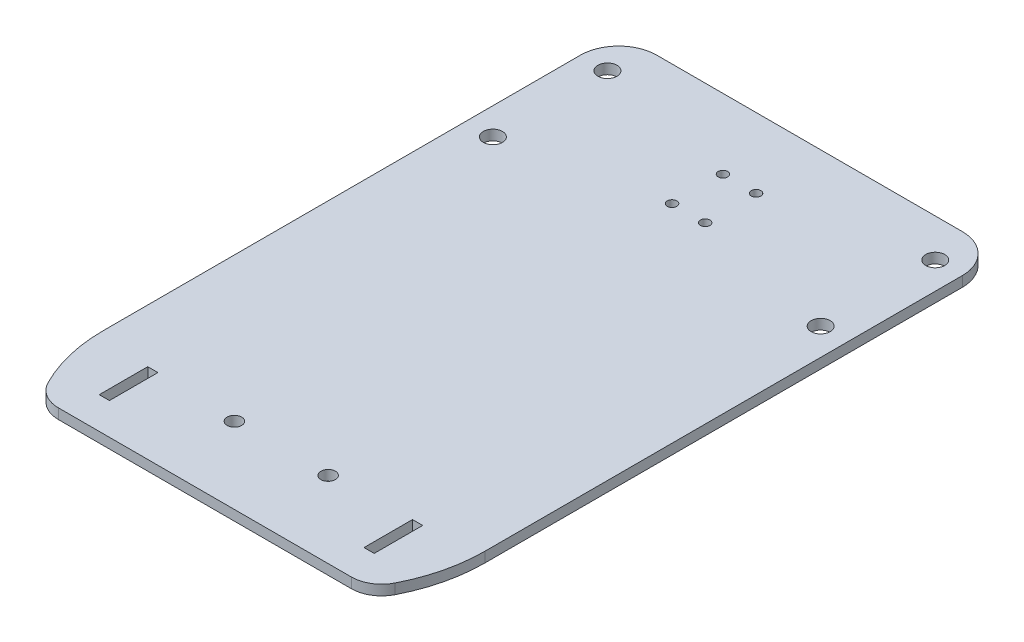
SolidWorks part; units mm, degrees
other "main"
material "Skleněné vlákno-A"
ref_plane "Přední rovina" through (0, 0, 0) normal (0, 0, 1) x (1, 0, 0)
ref_plane "Horní rovina" through (0, 0, 0) normal (0, 1, 0) x (1, 0, 0)
ref_plane "Pravá rovina" through (0, 0, 0) normal (1, 0, 0) x (0, 0, -1)
sketch "Skica1" plane through (0, 0, 0) normal (0, 1, 0) x (1, 0, 0)
  line L1 (-30, 0) -> (30, 0)
  line L2 (-30, 0) -> (-30, -95)
  line L3 (-30, -95) -> (30, -95)
  line L4 (30, 0) -> (30, -95)
  dimension "D1" = 60
  dimension "D2" = 95
extrude "Přidat vysunutím1" add sketch "Skica1" along normal mid plane 1.6
sketch "Skica3" plane through (0, 0.8, 0) normal (0, 1, 0) x (1, 0, 0)
  line L0 (-23, -81) -> (-30, -81) construction
  line L1 (-30, 0) -> (-30, -95) construction
  line L2 (-30, -95) -> (30, -95) construction
  line L3 (-23, -81) -> (-23, -95) construction
  line L4 (0, -95) -> (0, 0) construction
  line L5 (30, 0) -> (-30, 0) construction
  line L6 (-24, 0) -> (24, 0)
  line L7 (-30, -95) -> (30, -95) construction
  line L8 (-23, -95) -> (23, -95)
  line L9 (-30, -81) -> (-30, -6)
  line L10 (30, -81) -> (30, -6)
  arc A0 (-24, 0) -> (-30, -6) centre (-24, -6) ccw
  arc A1 (24, 0) -> (30, -6) centre (24, -6) cw
  arc A2 (-23, -95) -> (-27.2472, -92.4045) centre (-23, -90.2273) cw
  arc A3 (-27.2472, -92.4045) -> (-30, -81) centre (-5, -81) cw
  arc A4 (27.2472, -92.4045) -> (30, -81) centre (5, -81) ccw
  arc A5 (23, -95) -> (27.2472, -92.4045) centre (23, -90.2273) ccw
  dimension "D3" = 6
  dimension "D4" = 25
  dimension "D1" = 14
  dimension "D2" = 7
extrude "Odebrat vysunutím2" cut sketch "Skica3" against normal through all flip side to cut
sketch "Skica2" plane through (0, 0.8, 0) normal (0, 1, 0) x (1, 0, 0)
  line L1 (-20, -82.38) -> (-21.6, -82.38)
  line L2 (-20, -82.38) -> (-20, -90)
  line L3 (-20, -90) -> (-21.6, -90)
  line L4 (-21.6, -82.38) -> (-21.6, -90)
  line L5 (-23, -95) -> (23, -95) construction
  line L6 (0, 0) -> (0, -167.2259) construction
  line L7 (24, 0) -> (-24, 0) construction
  line L8 (21.6, -82.38) -> (21.6, -90)
  line L9 (20, -90) -> (21.6, -90)
  line L10 (20, -82.38) -> (20, -90)
  line L11 (20, -82.38) -> (21.6, -82.38)
  dimension "D1" = 40
  dimension "D2" = 1.6
  dimension "D3" = 7.62
  dimension "D4" = 5
extrude "Odebrat vysunutím1" cut sketch "Skica2" against normal through all
sketch "Skica4" plane through (0, 0.8, 0) normal (0, 1, 0) x (1, 0, 0)
  line L0 (0, 0) -> (0, -25.1622) construction
  circle A0 centre (-25.75, -6) radius 1.5
  circle A1 centre (-25.75, -24) radius 1.5
  circle A2 centre (-25.75, -24) radius 1.25 construction
  circle A3 centre (-25.75, -6) radius 1.25 construction
  circle A4 centre (25.75, -24) radius 1.5
  circle A5 centre (25.75, -6) radius 1.5
  dimension "D1" = 3
extrude "Odebrat vysunutím3" cut sketch "Skica4" against normal through all
sketch "Skica5" plane through (0, -0.8, 0) normal (0, -1, 0) x (1, 0, 0)
  circle A0 centre (-7.366, 83) radius 1.143 construction
  circle A1 centre (-7.366, 83) radius 1.143
  circle A2 centre (7.366, 83) radius 1.143 construction
  circle A3 centre (7.366, 83) radius 1.143
extrude "Odebrat vysunutím4" cut sketch "Skica5" against normal through all
sketch "Skica6" plane through (0, -0.8, 0) normal (0, -1, 0) x (1, 0, 0)
  line L0 (-20, 88.73) -> (-18.73, 88.73)
  line L1 (-20, 86.19) -> (-18.73, 86.19)
  line L3 (-20, 83.65) -> (-18.73, 83.65)
  line L4 (-20, 95.9658) -> (-18.73, 95.9658) construction
  line L5 (-20.8, 82.38) -> (-20.8, 88.1097) construction
  line L6 (-20, 82.38) -> (-21.6, 82.38) construction
  line L7 (-21.6, 83.65) -> (-22.87, 83.65)
  line L8 (-21.6, 86.19) -> (-22.87, 86.19)
  line L9 (-21.6, 88.73) -> (-22.87, 88.73)
  line L10 (0, 0) -> (0, 32.2699) construction
  line L11 (21.6, 88.73) -> (22.87, 88.73)
  line L12 (21.6, 86.19) -> (22.87, 86.19)
  line L13 (21.6, 83.65) -> (22.87, 83.65)
  line L14 (20, 83.65) -> (18.73, 83.65)
  line L15 (20, 86.19) -> (18.73, 86.19)
  line L16 (20, 88.73) -> (18.73, 88.73)
sketch "Skica7" [suppressed] plane through (0, 0.8, 0) normal (0, 1, 0) x (1, 0, 0)
  line L0 (-26.5, -29) -> (26.5, -29) construction
  line L1 (-29.5, -27) -> (29.5, -27)
  line L2 (-29.5, -27) -> (-29.5, -61)
  line L3 (-29.5, -61) -> (29.5, -61)
  line L4 (29.5, -27) -> (29.5, -61)
  line L5 (26.5, -59) -> (-26.5, -59) construction
  line L6 (-27.5, -58) -> (-27.5, -30) construction
  line L7 (-30, -6) -> (-30, -81) construction
  line L8 (27.5, -30) -> (27.5, -58) construction
  line L9 (-19, -22.5) -> (-29.5, -22.5) construction
  line L10 (-4.8, -7.5) -> (-21.5, -7.5)
  line L11 (-4.8, -7.5) -> (-4.8, -22.5)
  line L12 (-4.8, -22.5) -> (-21.5, -22.5)
  line L13 (-21.5, -7.5) -> (-21.5, -5.95) construction
  line L14 (-29.5, -7.5) -> (-19, -7.5) construction
  line L15 (-4.8, -17.5) -> (-4.8, -12.5) construction
  line L16 (-21.5, -7.5) -> (-21.5, -5.95)
  line L17 (-30, -6) -> (-30, -24.05)
  line L18 (-21.5, -24.05) -> (-21.5, -22.5) construction
  line L19 (-21.5, -24.05) -> (-21.5, -22.5)
  line L20 (0, 0) -> (0, -32.2699) construction
  line L21 (21.5, -24.05) -> (21.5, -22.5)
  line L22 (30, -6) -> (30, -24.05)
  line L23 (21.5, -7.5) -> (21.5, -5.95)
  line L24 (4.8, -22.5) -> (21.5, -22.5)
  line L25 (4.8, -7.5) -> (4.8, -22.5)
  line L26 (4.8, -7.5) -> (21.5, -7.5)
  line L27 (-7.0059, -86.4171) -> (-8.7453, -85.4298) construction
  line L28 (-7.0059, -86.4171) -> (-8.7453, -85.4298)
  line L29 (-8.7453, -80.5702) -> (-7.0059, -79.5829) construction
  line L30 (7.0059, -79.5829) -> (8.7453, -80.5702) construction
  line L31 (8.7453, -85.4298) -> (7.0059, -86.4171) construction
  line L32 (-8.7453, -80.5702) -> (-7.0059, -79.5829)
  line L33 (7.0059, -79.5829) -> (8.7453, -80.5702)
  line L34 (8.7453, -85.4298) -> (7.0059, -86.4171)
  arc A0 (-21.5, -5.95) -> (-30, -5.95) centre (-25.75, -5.95) ccw construction
  arc A1 (-21.5, -5.95) -> (-30, -5.95) centre (-25.75, -5.95) ccw
  arc A2 (-30, -24.05) -> (-21.5, -24.05) centre (-25.75, -24.05) ccw construction
  arc A3 (-30, -24.05) -> (-21.5, -24.05) centre (-25.75, -24.05) ccw
  arc A4 (30, -24.05) -> (21.5, -24.05) centre (25.75, -24.05) cw
  arc A5 (21.5, -5.95) -> (30, -5.95) centre (25.75, -5.95) cw
  arc A6 (-8.7453, -80.5702) -> (-8.7453, -85.4298) centre (-7.366, -83) ccw construction
  arc A7 (-7.0059, -79.5829) -> (-5.6072, -78.4041) centre (-9.4742, -75.2346) ccw construction
  arc A8 (5.6072, -78.4041) -> (-5.6072, -78.4041) centre (0, -83) ccw construction
  arc A9 (5.6072, -78.4041) -> (7.0059, -79.5829) centre (9.4742, -75.2346) ccw construction
  arc A10 (8.7453, -85.4298) -> (8.7453, -80.5702) centre (7.366, -83) ccw construction
  arc A11 (7.0059, -86.4171) -> (5.6072, -87.5959) centre (9.4742, -90.7654) ccw construction
  arc A12 (-5.6072, -87.5959) -> (5.6072, -87.5959) centre (0, -83) ccw construction
  arc A13 (-5.6072, -87.5959) -> (-7.0059, -86.4171) centre (-9.4742, -90.7654) ccw construction
  arc A14 (-8.7453, -80.5702) -> (-8.7453, -85.4298) centre (-7.366, -83) ccw
  arc A15 (-7.0059, -79.5829) -> (-5.6072, -78.4041) centre (-9.4742, -75.2346) ccw
  arc A16 (5.6072, -78.4041) -> (-5.6072, -78.4041) centre (0, -83) ccw
  arc A17 (5.6072, -78.4041) -> (7.0059, -79.5829) centre (9.4742, -75.2346) ccw
  arc A18 (8.7453, -85.4298) -> (8.7453, -80.5702) centre (7.366, -83) ccw
  arc A19 (7.0059, -86.4171) -> (5.6072, -87.5959) centre (9.4742, -90.7654) ccw
  arc A20 (-5.6072, -87.5959) -> (5.6072, -87.5959) centre (0, -83) ccw
  arc A21 (-5.6072, -87.5959) -> (-7.0059, -86.4171) centre (-9.4742, -90.7654) ccw
  dimension "D1" = 2
  dimension "D2" = 2
  dimension "D3" = 2
  dimension "D4" = 2
sketch "Skica8" plane through (0, 0.8, 0) normal (0, 1, 0) x (1, 0, 0)
  line L0 (-23.95, -15) -> (-16.1139, -15) construction
  line L1 (-5.6, -11.9) -> (-5.6, -9) construction
  line L3 (0, 0) -> (0, -32.2699) construction
  circle A0 centre (-2.6, -11) radius 0.75
  circle A1 centre (-2.6, -19) radius 0.75
  circle A2 centre (2.6, -19) radius 0.75
  circle A3 centre (2.6, -11) radius 0.75
  dimension "D1" = 8
  dimension "D2" = 1.5
  dimension "D3" = 3
extrude "Odebrat vysunutím5" cut sketch "Skica8" against normal through all
